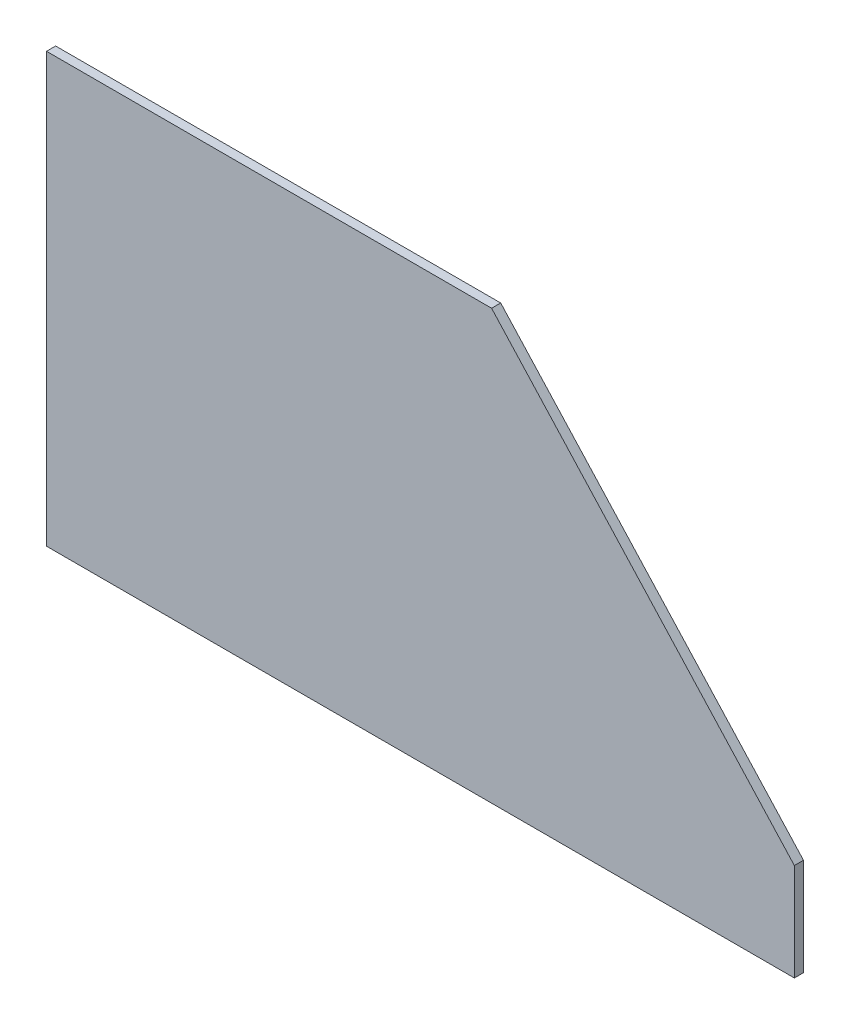
SolidWorks part; units mm, degrees
ref_plane "Front Plane" through (0, 0, 0) normal (0, 0, 1) x (1, 0, 0)
ref_plane "Top Plane" through (0, 0, 0) normal (0, 1, 0) x (1, 0, 0)
ref_plane "Right Plane" through (0, 0, 0) normal (1, 0, 0) x (0, 0, -1)
sketch "Sketch1" plane through (0, 0, 0) normal (0, 0, 1) x (1, 0, 0)
  line L0 (0, 0) -> (520.7, 0)
  line L1 (520.7, 0) -> (520.7, 67.818)
  line L2 (520.7, 67.818) -> (309.88, 298.45)
  line L3 (309.88, 298.45) -> (0, 298.45)
  line L4 (0, 298.45) -> (0, 0)
  dimension "D1" = 520.7
  dimension "D2" = 298.45
  dimension "D3" = 309.88
  dimension "D4" = 67.818
  dimension "D5" = 312.4679
extrude "Boss-Extrude1" add sketch "Sketch1" along normal blind 6.35
